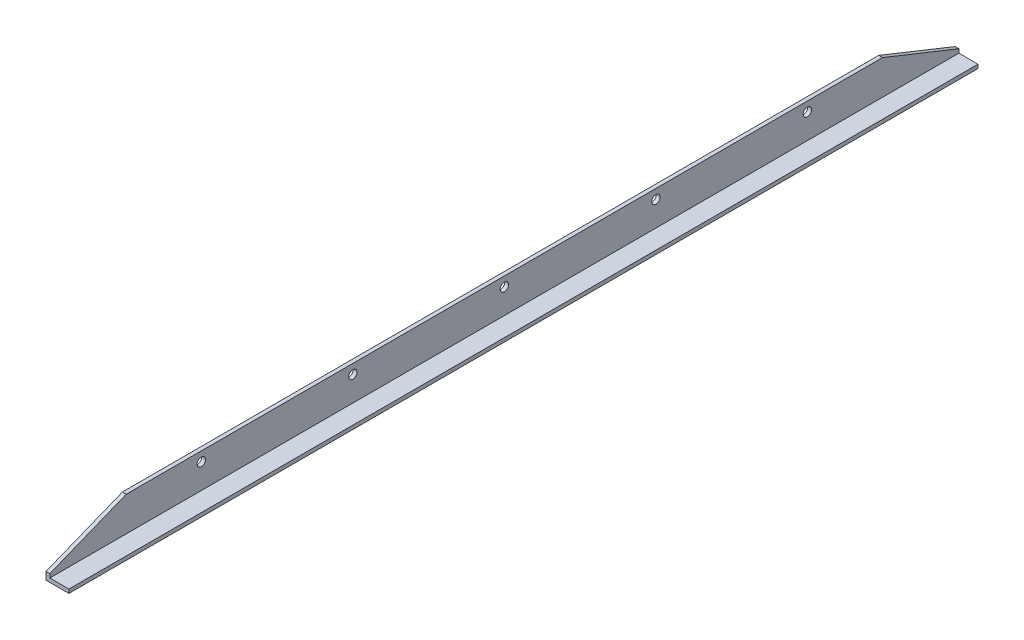
SolidWorks part; units mm, degrees
material "Plain Carbon Steel"
ref_plane "Front Plane" through (0, 0, 0) normal (0, 0, 1) x (1, 0, 0)
ref_plane "Top Plane" through (0, 0, 0) normal (0, 1, 0) x (1, 0, 0)
ref_plane "Right Plane" through (0, 0, 0) normal (1, 0, 0) x (0, 0, -1)
sketch "Sketch1" plane through (0, 0, 0) normal (0, 0, 1) x (1, 0, 0)
  line L0 (0, 63.5) -> (0, 0)
  line L1 (0, 0) -> (38.1, 0)
  dimension "D1" = 63.5
  dimension "D2" = 38.1
extrude "Extrude-Thin1" add sketch "Sketch1" along normal blind 1511.3 thin thin type one direction reverse wall 6.35
hole_wizard "1/2 Clearance Hole1" positions "Sketch2" profile "Sketch3" hole size "1/2" standard "ANSI Inch"
sketch "Sketch2" plane through (0, 0, 0) normal (-1, 0, 0) x (0, 0, 1)
  line L0 (1511.3, 47.625) -> (1259.4167, 47.625) construction
  line L2 (1259.4167, 47.625) -> (1007.5333, 47.625) construction
  line L3 (1007.5333, 47.625) -> (755.65, 47.625) construction
  line L4 (755.65, 47.625) -> (503.7667, 47.625) construction
  line L5 (503.7667, 47.625) -> (251.8833, 47.625) construction
  line L6 (251.8833, 47.625) -> (0, 47.625) construction
  line L8 (1511.3, 63.5) -> (0, 63.5) construction
  line L9 (0, 63.5) -> (0, 0) construction
  point P0 (1259.4167, 47.625)
  point P2 (1007.5333, 47.625)
  point P4 (755.65, 47.625)
  point P6 (503.7667, 47.625)
  point P8 (251.8833, 47.625)
  point P41 (0, 31.75)
  dimension "D1" = 15.875
sketch "Sketch3" plane through (0, 47.625, 1259.4167) normal (0, 1, 0) x (0, 0, 1)
  line L0 (0, 0) -> (0, 20.6834)
  line L1 (0, 20.6834) -> (6.9456, 16.51)
  line L2 (6.9456, 16.51) -> (6.9456, 0)
  line L5 (6.9456, 0) -> (0, 0)
  line L10 (0, 20.6834) -> (-6.9456, 16.51) construction
  line L11 (0, -6.35) -> (0, 107.95) construction
  dimension "Hole Dia." = 13.8913
  dimension "Hole Depth" = 16.51
  dimension "Drill Angle" = 118
sketch "Sketch4" plane through (0, 0, 0) normal (-1, 0, 0) x (0, 0, 1)
  line L0 (1511.3, 12.7) -> (1384.3, 63.5)
  line L1 (1511.3, 63.5) -> (1511.3, 0) construction
  line L2 (1511.3, 63.5) -> (0, 63.5) construction
  line L3 (1384.3, 63.5) -> (1511.3, 63.5)
  line L4 (1511.3, 63.5) -> (1511.3, 12.7)
  line L5 (127, 63.5) -> (0, 12.7)
  line L6 (0, 63.5) -> (0, 0) construction
  line L7 (0, 12.7) -> (0, 63.5)
  line L8 (0, 63.5) -> (127, 63.5)
  dimension "D1" = 12.7
  dimension "D2" = 127
extrude "Cut-Extrude1" cut sketch "Sketch4" against normal up to surface (6.35 mm away) up to face at (6.35, 47.625, 1252.471)
